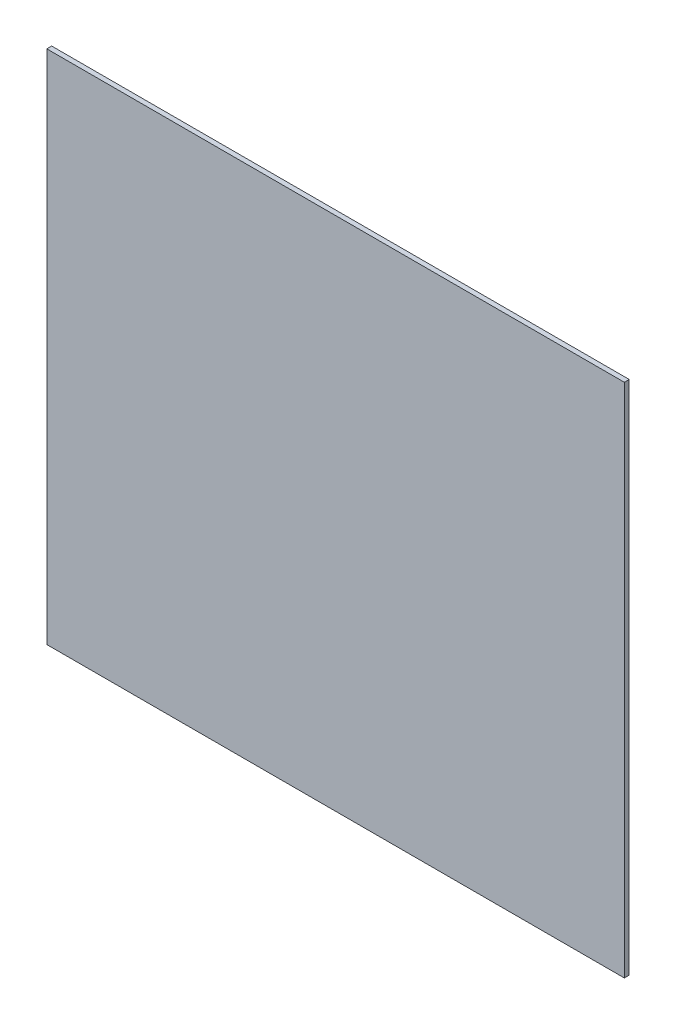
SolidWorks part; units mm, degrees
ref_plane "Plan de face" through (0, 0, 0) normal (0, 0, 1) x (1, 0, 0)
ref_plane "Plan de dessus" through (0, 0, 0) normal (0, 1, 0) x (1, 0, 0)
ref_plane "Plan de droite" through (0, 0, 0) normal (1, 0, 0) x (0, 0, -1)
sketch "Esquisse1" plane through (0, 0, 0) normal (0, 0, 1) x (1, 0, 0)
  line L1 (-168.2466, 86.5616) -> (187.7534, 86.5616)
  line L2 (-168.2466, 86.5616) -> (-168.2466, -231.4384)
  line L3 (-168.2466, -231.4384) -> (187.7534, -231.4384)
  line L4 (187.7534, 86.5616) -> (187.7534, -231.4384)
  dimension "D1" = 356
  dimension "D2" = 318
extrude "Boss.-Extru.1" add sketch "Esquisse1" along normal blind 3
